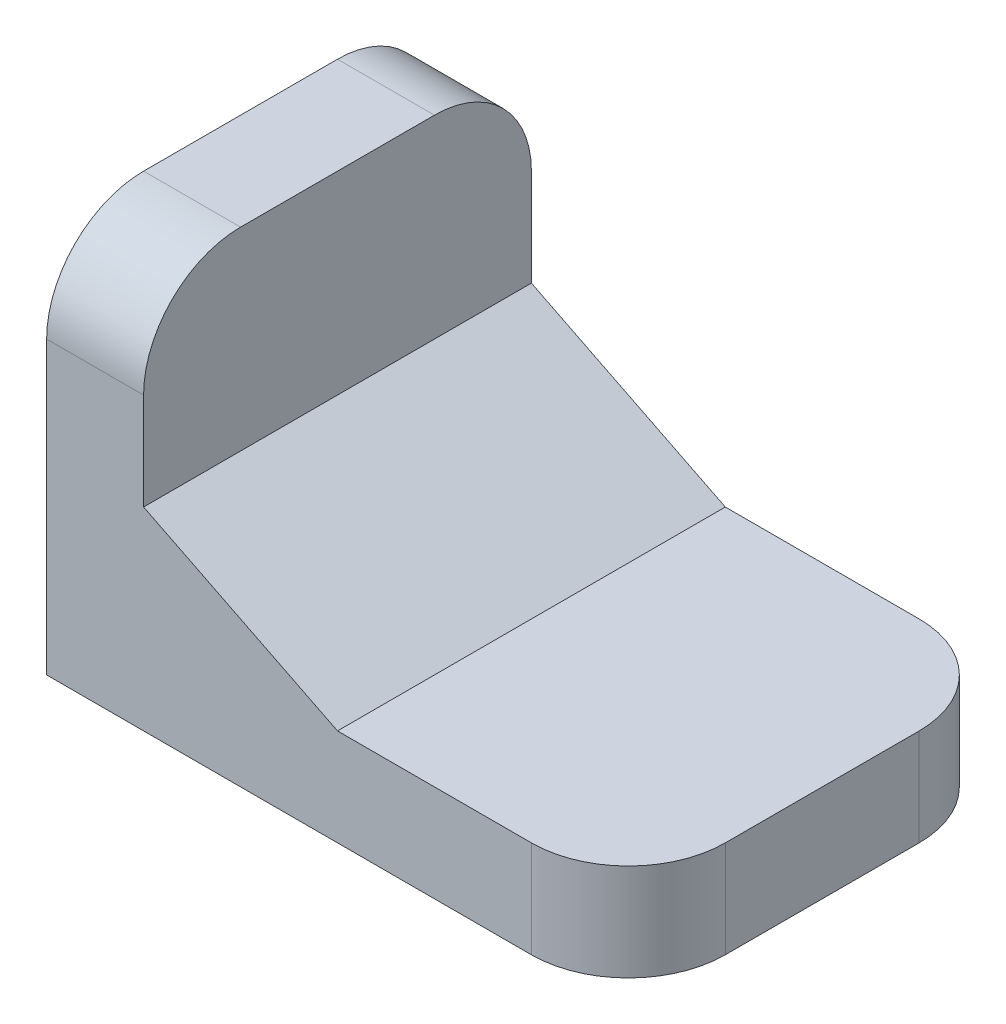
SolidWorks part; units mm, degrees
ref_plane "Front Plane" through (0, 0, 0) normal (0, 0, 1) x (1, 0, 0)
ref_plane "Top Plane" through (0, 0, 0) normal (0, 1, 0) x (1, 0, 0)
ref_plane "Right Plane" through (0, 0, 0) normal (1, 0, 0) x (0, 0, -1)
sketch "Sketch1" plane through (0, 0, 0) normal (0, 0, 1) x (1, 0, 0)
  line L0 (-47.5385, 12.3077) -> (-37.5385, 12.3077)
  line L1 (-37.5385, 12.3077) -> (-37.5385, -7.6923)
  line L2 (-37.5385, -7.6923) -> (-17.5385, -17.6923)
  line L3 (-17.5385, -17.6923) -> (12.4615, -17.6923)
  line L4 (12.4615, -17.6923) -> (12.4615, -27.6923)
  line L5 (12.4615, -27.6923) -> (-47.5385, -27.6923)
  line L6 (-47.5385, -27.6923) -> (-47.5385, 12.3077)
  dimension "D1" = 10
  dimension "D2" = 10
  dimension "D3" = 10
  dimension "D4" = 40
  dimension "D5" = 60
  dimension "D6" = 30
extrude "Boss-Extrude1" add sketch "Sketch1" along normal blind 40
sketch "Sketch2" plane through (-47.5385, 0, 0) normal (-1, 0, 0) x (0, 0, 1)
  line L0 (0, 2.3077) -> (0, -27.6923)
  line L1 (0, -27.6923) -> (40, -27.6923)
  line L2 (40, -27.6923) -> (40, 2.3077)
  line L3 (30, 12.3077) -> (10, 12.3077)
  arc A0 (40, 2.3077) -> (30, 12.3077) centre (30, 2.3077) ccw
  arc A1 (10, 12.3077) -> (0, 2.3077) centre (10, 2.3077) ccw
  point P10 (40, 12.3077)
  point P13 (0, 12.3077)
  dimension "D1" = 10
extrude "Cut-Extrude1" cut sketch "Sketch2" against normal blind 40 flip side to cut
sketch "Sketch3" plane through (0, -27.6923, 0) normal (0, -1, 0) x (1, 0, 0)
  line L0 (-47.5385, 40) -> (2.4615, 40)
  line L1 (12.4615, 30) -> (12.4615, 10)
  line L2 (2.4615, 0) -> (-47.5385, 0)
  line L3 (-47.5385, 0) -> (-47.5385, 40)
  arc A0 (2.4615, 40) -> (12.4615, 30) centre (2.4615, 30) cw
  arc A1 (12.4615, 10) -> (2.4615, 0) centre (2.4615, 10) cw
  point P10 (12.4615, 40)
  point P13 (12.4615, 0)
  dimension "D1" = 10
extrude "Cut-Extrude2" cut sketch "Sketch3" against normal blind 40 flip side to cut
